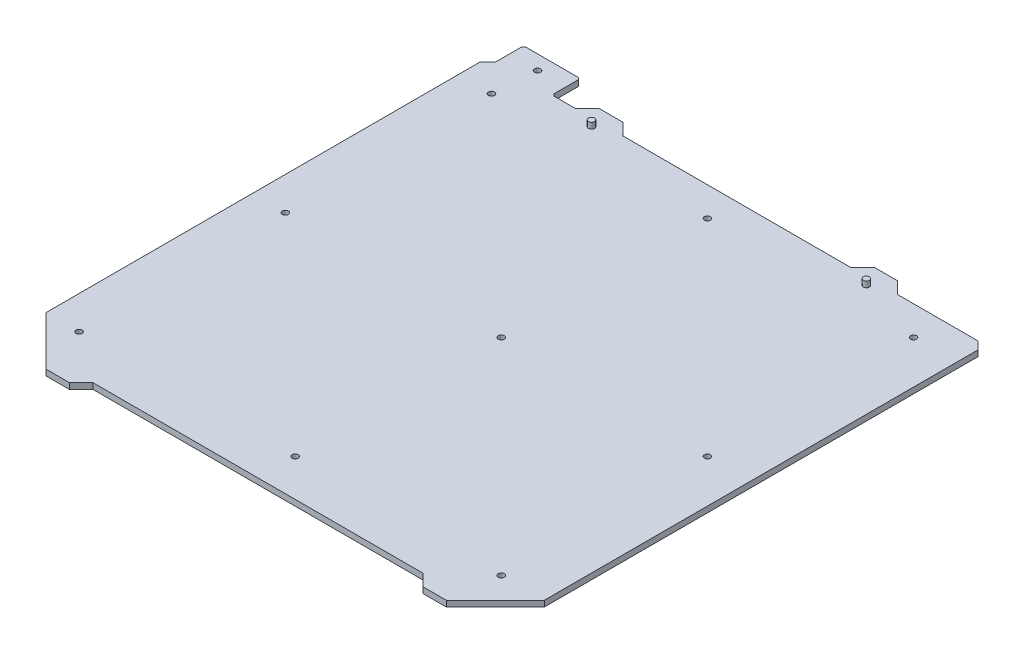
SolidWorks part; units mm, degrees
ref_plane "Front Plane" through (0, 0, 0) normal (0, 0, 1) x (1, 0, 0)
ref_plane "Top Plane" through (0, 0, 0) normal (0, 1, 0) x (1, 0, 0)
ref_plane "Right Plane" through (0, 0, 0) normal (1, 0, 0) x (0, 0, -1)
sketch "Sketch1" plane through (0, 0, 0) normal (0, 1, 0) x (1, 0, 0)
  line L0 (32.0022, 249.45) -> (32.0044, 249.45)
  line L1 (32.0044, 249.45) -> (32.0107, 249.448)
  line L2 (32.0107, 249.448) -> (32.0171, 249.447)
  line L3 (32.0171, 249.447) -> (32.019, 249.446)
  line L4 (32.019, 249.446) -> (32.0211, 249.445)
  line L5 (32.0211, 249.445) -> (32.0265, 249.442)
  line L6 (32.0265, 249.442) -> (32.0321, 249.438)
  line L7 (32.0321, 249.438) -> (32.0336, 249.437)
  line L8 (32.0336, 249.437) -> (32.0354, 249.435)
  line L9 (32.0354, 249.435) -> (33.0354, 248.435)
  line L10 (33.0354, 248.435) -> (33.0366, 248.434)
  line L11 (33.0366, 248.434) -> (33.0383, 248.432)
  line L12 (33.0383, 248.432) -> (33.0416, 248.426)
  line L13 (33.0416, 248.426) -> (33.0453, 248.421)
  line L14 (33.0453, 248.421) -> (33.0459, 248.419)
  line L15 (33.0459, 248.419) -> (33.047, 248.417)
  line L16 (33.047, 248.417) -> (33.0481, 248.411)
  line L17 (33.0481, 248.411) -> (33.0498, 248.404)
  line L18 (33.0498, 248.404) -> (33.0496, 248.402)
  line L19 (33.0496, 248.402) -> (33.05, 248.4)
  line L20 (33.05, 248.4) -> (33.05, 236.021)
  line L21 (33.05, 236.021) -> (33.9751, 235.096)
  line L22 (33.9751, 235.096) -> (34, 235.1)
  line L23 (34, 235.1) -> (45, 235.1)
  line L24 (45, 235.1) -> (45.0249, 235.096)
  line L25 (45.0249, 235.096) -> (50.9646, 241.035)
  line L26 (50.9646, 241.035) -> (50.9664, 241.037)
  line L27 (50.9664, 241.037) -> (50.9679, 241.038)
  line L28 (50.9679, 241.038) -> (50.9735, 241.042)
  line L29 (50.9735, 241.042) -> (50.9789, 241.045)
  line L30 (50.9789, 241.045) -> (50.981, 241.046)
  line L31 (50.981, 241.046) -> (50.9829, 241.047)
  line L32 (50.9829, 241.047) -> (50.9893, 241.048)
  line L33 (50.9893, 241.048) -> (50.9956, 241.05)
  line L34 (50.9956, 241.05) -> (50.9978, 241.05)
  line L35 (50.9978, 241.05) -> (51, 241.05)
  line L36 (51, 241.05) -> (63, 241.05)
  line L37 (63, 241.05) -> (63.0022, 241.05)
  line L38 (63.0022, 241.05) -> (63.0044, 241.05)
  line L39 (63.0044, 241.05) -> (63.0107, 241.048)
  line L40 (63.0107, 241.048) -> (63.0171, 241.047)
  line L41 (63.0171, 241.047) -> (63.019, 241.046)
  line L42 (63.019, 241.046) -> (63.0211, 241.045)
  line L43 (63.0211, 241.045) -> (63.0265, 241.042)
  line L44 (63.0265, 241.042) -> (63.0321, 241.038)
  line L45 (63.0321, 241.038) -> (63.0336, 241.037)
  line L46 (63.0336, 241.037) -> (63.0354, 241.035)
  line L47 (63.0354, 241.035) -> (68.9751, 235.096)
  line L48 (68.9751, 235.096) -> (69, 235.1)
  line L49 (69, 235.1) -> (185, 235.1)
  line L50 (185, 235.1) -> (185.025, 235.096)
  line L51 (185.025, 235.096) -> (190.965, 241.035)
  line L52 (190.965, 241.035) -> (190.966, 241.037)
  line L53 (190.966, 241.037) -> (190.968, 241.038)
  line L54 (190.968, 241.038) -> (190.974, 241.042)
  line L55 (190.974, 241.042) -> (190.979, 241.045)
  line L56 (190.979, 241.045) -> (190.981, 241.046)
  line L57 (190.981, 241.046) -> (190.983, 241.047)
  line L58 (190.983, 241.047) -> (190.989, 241.048)
  line L59 (190.989, 241.048) -> (190.996, 241.05)
  line L60 (190.996, 241.05) -> (190.998, 241.05)
  line L61 (190.998, 241.05) -> (191, 241.05)
  line L62 (191, 241.05) -> (203, 241.05)
  line L63 (203, 241.05) -> (203.002, 241.05)
  line L64 (203.002, 241.05) -> (203.004, 241.05)
  line L65 (203.004, 241.05) -> (203.011, 241.048)
  line L66 (203.011, 241.048) -> (203.017, 241.047)
  line L67 (203.017, 241.047) -> (203.019, 241.046)
  line L68 (203.019, 241.046) -> (203.021, 241.045)
  line L69 (203.021, 241.045) -> (203.026, 241.042)
  line L70 (203.026, 241.042) -> (203.032, 241.038)
  line L71 (203.032, 241.038) -> (203.034, 241.037)
  line L72 (203.034, 241.037) -> (203.035, 241.035)
  line L73 (203.035, 241.035) -> (208.975, 235.096)
  line L74 (208.975, 235.096) -> (209, 235.1)
  line L75 (209, 235.1) -> (250, 235.1)
  line L76 (250, 235.1) -> (250.004, 235.099)
  line L77 (250.004, 235.099) -> (250.009, 235.1)
  line L78 (250.009, 235.1) -> (250.021, 235.096)
  line L79 (250.021, 235.096) -> (250.034, 235.094)
  line L80 (250.034, 235.094) -> (250.038, 235.092)
  line L81 (250.038, 235.092) -> (250.042, 235.091)
  line L82 (250.042, 235.091) -> (250.053, 235.083)
  line L83 (250.053, 235.083) -> (250.064, 235.077)
  line L84 (250.064, 235.077) -> (250.067, 235.073)
  line L85 (250.067, 235.073) -> (250.071, 235.071)
  line L86 (250.071, 235.071) -> (254.071, 231.071)
  line L87 (254.071, 231.071) -> (254.073, 231.067)
  line L88 (254.073, 231.067) -> (254.077, 231.064)
  line L89 (254.077, 231.064) -> (254.083, 231.053)
  line L90 (254.083, 231.053) -> (254.091, 231.042)
  line L91 (254.091, 231.042) -> (254.092, 231.038)
  line L92 (254.092, 231.038) -> (254.094, 231.034)
  line L93 (254.094, 231.034) -> (254.096, 231.021)
  line L94 (254.096, 231.021) -> (254.1, 231.009)
  line L95 (254.1, 231.009) -> (254.099, 231.004)
  line L96 (254.099, 231.004) -> (254.1, 231)
  line L97 (254.1, 231) -> (254.1, 10)
  line L98 (254.1, 10) -> (254.099, 9.9957)
  line L99 (254.099, 9.9957) -> (254.1, 9.9913)
  line L100 (254.1, 9.9913) -> (254.096, 9.9787)
  line L101 (254.096, 9.9787) -> (254.094, 9.9658)
  line L102 (254.094, 9.9658) -> (254.092, 9.962)
  line L103 (254.092, 9.962) -> (254.091, 9.9577)
  line L104 (254.091, 9.9577) -> (254.083, 9.947)
  line L105 (254.083, 9.947) -> (254.077, 9.9357)
  line L106 (254.077, 9.9357) -> (254.073, 9.9329)
  line L107 (254.073, 9.9329) -> (254.071, 9.9293)
  line L108 (254.071, 9.9293) -> (229.071, -15.0707)
  line L109 (229.071, -15.0707) -> (229.067, -15.0732)
  line L110 (229.067, -15.0732) -> (229.064, -15.0766)
  line L111 (229.064, -15.0766) -> (229.053, -15.0831)
  line L112 (229.053, -15.0831) -> (229.042, -15.0906)
  line L113 (229.042, -15.0906) -> (229.038, -15.0918)
  line L114 (229.038, -15.0918) -> (229.034, -15.094)
  line L115 (229.034, -15.094) -> (229.021, -15.0962)
  line L116 (229.021, -15.0962) -> (229.009, -15.0996)
  line L117 (229.009, -15.0996) -> (229.004, -15.0992)
  line L118 (229.004, -15.0992) -> (229, -15.1)
  line L119 (229, -15.1) -> (217, -15.1)
  line L120 (217, -15.1) -> (216.996, -15.0992)
  line L121 (216.996, -15.0992) -> (216.991, -15.0996)
  line L122 (216.991, -15.0996) -> (216.979, -15.0962)
  line L123 (216.979, -15.0962) -> (216.966, -15.094)
  line L124 (216.966, -15.094) -> (216.962, -15.0918)
  line L125 (216.962, -15.0918) -> (216.958, -15.0906)
  line L126 (216.958, -15.0906) -> (216.947, -15.0831)
  line L127 (216.947, -15.0831) -> (216.936, -15.0766)
  line L128 (216.936, -15.0766) -> (216.933, -15.0732)
  line L129 (216.933, -15.0732) -> (216.929, -15.0707)
  line L130 (216.929, -15.0707) -> (210.959, -9.1)
  line L131 (210.959, -9.1) -> (43.0414, -9.1)
  line L132 (43.0414, -9.1) -> (37.0707, -15.0707)
  line L133 (37.0707, -15.0707) -> (37.0671, -15.0732)
  line L134 (37.0671, -15.0732) -> (37.0643, -15.0766)
  line L135 (37.0643, -15.0766) -> (37.053, -15.0831)
  line L136 (37.053, -15.0831) -> (37.0423, -15.0906)
  line L137 (37.0423, -15.0906) -> (37.038, -15.0918)
  line L138 (37.038, -15.0918) -> (37.0342, -15.094)
  line L139 (37.0342, -15.094) -> (37.0213, -15.0962)
  line L140 (37.0213, -15.0962) -> (37.0087, -15.0996)
  line L141 (37.0087, -15.0996) -> (37.0043, -15.0992)
  line L142 (37.0043, -15.0992) -> (37, -15.1)
  line L143 (37, -15.1) -> (25, -15.1)
  line L144 (25, -15.1) -> (24.9957, -15.0992)
  line L145 (24.9957, -15.0992) -> (24.9913, -15.0996)
  line L146 (24.9913, -15.0996) -> (24.9787, -15.0962)
  line L147 (24.9787, -15.0962) -> (24.9658, -15.094)
  line L148 (24.9658, -15.094) -> (24.962, -15.0918)
  line L149 (24.962, -15.0918) -> (24.9577, -15.0906)
  line L150 (24.9577, -15.0906) -> (24.947, -15.0831)
  line L151 (24.947, -15.0831) -> (24.9357, -15.0766)
  line L152 (24.9357, -15.0766) -> (24.9329, -15.0732)
  line L153 (24.9329, -15.0732) -> (24.9293, -15.0707)
  line L154 (24.9293, -15.0707) -> (-0.0707, 9.9293)
  line L155 (-0.0707, 9.9293) -> (-0.0732, 9.9329)
  line L156 (-0.0732, 9.9329) -> (-0.0766, 9.9357)
  line L157 (-0.0766, 9.9357) -> (-0.0831, 9.947)
  line L158 (-0.0831, 9.947) -> (-0.0906, 9.9577)
  line L159 (-0.0906, 9.9577) -> (-0.0918, 9.962)
  line L160 (-0.0918, 9.962) -> (-0.094, 9.9658)
  line L161 (-0.094, 9.9658) -> (-0.0962, 9.9787)
  line L162 (-0.0962, 9.9787) -> (-0.0996, 9.9913)
  line L163 (-0.0996, 9.9913) -> (-0.0992, 9.9957)
  line L164 (-0.0992, 9.9957) -> (-0.1, 10)
  line L165 (-0.1, 10) -> (-0.1, 231)
  line L166 (-0.1, 231) -> (-0.094, 231.034)
  line L167 (-0.094, 231.034) -> (-0.0766, 231.064)
  line L168 (-0.0766, 231.064) -> (-0.05, 231.087)
  line L169 (-0.05, 231.087) -> (-0.0174, 231.098)
  line L170 (-0.0174, 231.098) -> (0.0174, 231.098)
  line L171 (0.0174, 231.098) -> (0.025, 231.096)
  line L172 (0.025, 231.096) -> (3.95, 235.021)
  line L173 (3.95, 235.021) -> (3.95, 248.4)
  line L174 (3.95, 248.4) -> (3.9504, 248.402)
  line L175 (3.9504, 248.402) -> (3.9502, 248.404)
  line L176 (3.9502, 248.404) -> (3.9519, 248.411)
  line L177 (3.9519, 248.411) -> (3.953, 248.417)
  line L178 (3.953, 248.417) -> (3.9541, 248.419)
  line L179 (3.9541, 248.419) -> (3.9547, 248.421)
  line L180 (3.9547, 248.421) -> (3.9584, 248.426)
  line L181 (3.9584, 248.426) -> (3.9617, 248.432)
  line L182 (3.9617, 248.432) -> (3.9634, 248.434)
  line L183 (3.9634, 248.434) -> (3.9646, 248.435)
  line L184 (3.9646, 248.435) -> (4.9646, 249.435)
  line L185 (4.9646, 249.435) -> (4.9665, 249.437)
  line L186 (4.9665, 249.437) -> (4.9679, 249.438)
  line L187 (4.9679, 249.438) -> (4.9735, 249.442)
  line L188 (4.9735, 249.442) -> (4.9789, 249.445)
  line L189 (4.9789, 249.445) -> (4.981, 249.446)
  line L190 (4.981, 249.446) -> (4.9829, 249.447)
  line L191 (4.9829, 249.447) -> (4.9893, 249.448)
  line L192 (4.9893, 249.448) -> (4.9956, 249.45)
  line L193 (4.9956, 249.45) -> (4.9978, 249.45)
  line L194 (4.9978, 249.45) -> (5, 249.45)
  line L195 (5, 249.45) -> (32, 249.45)
  line L196 (32, 249.45) -> (32.0022, 249.45)
  line L197 (5.0207, 249.35) -> (4.05, 248.379)
  line L198 (4.05, 248.379) -> (4.05, 235)
  line L199 (4.05, 235) -> (4.0496, 234.998)
  line L200 (4.0496, 234.998) -> (4.0498, 234.996)
  line L201 (4.0498, 234.996) -> (4.0481, 234.989)
  line L202 (4.0481, 234.989) -> (4.047, 234.983)
  line L203 (4.047, 234.983) -> (4.0459, 234.981)
  line L204 (4.0459, 234.981) -> (4.0453, 234.979)
  line L205 (4.0453, 234.979) -> (4.0416, 234.974)
  line L206 (4.0416, 234.974) -> (4.0383, 234.968)
  line L207 (4.0383, 234.968) -> (4.0366, 234.966)
  line L208 (4.0366, 234.966) -> (4.0354, 234.965)
  line L209 (4.0354, 234.965) -> (0.0956, 231.025)
  line L210 (0.0956, 231.025) -> (0.1, 231)
  line L211 (0.1, 231) -> (0.1, 10.0414)
  line L212 (0.1, 10.0414) -> (25.0414, -14.9)
  line L213 (25.0414, -14.9) -> (36.9586, -14.9)
  line L214 (36.9586, -14.9) -> (42.9293, -8.9293)
  line L215 (42.9293, -8.9293) -> (42.9329, -8.9268)
  line L216 (42.9329, -8.9268) -> (42.9357, -8.9234)
  line L217 (42.9357, -8.9234) -> (42.947, -8.9169)
  line L218 (42.947, -8.9169) -> (42.9577, -8.9094)
  line L219 (42.9577, -8.9094) -> (42.962, -8.9082)
  line L220 (42.962, -8.9082) -> (42.9658, -8.906)
  line L221 (42.9658, -8.906) -> (42.9787, -8.9038)
  line L222 (42.9787, -8.9038) -> (42.9913, -8.9004)
  line L223 (42.9913, -8.9004) -> (42.9957, -8.9008)
  line L224 (42.9957, -8.9008) -> (43, -8.9)
  line L225 (43, -8.9) -> (211, -8.9)
  line L226 (211, -8.9) -> (211.004, -8.9008)
  line L227 (211.004, -8.9008) -> (211.009, -8.9004)
  line L228 (211.009, -8.9004) -> (211.021, -8.9038)
  line L229 (211.021, -8.9038) -> (211.034, -8.906)
  line L230 (211.034, -8.906) -> (211.038, -8.9082)
  line L231 (211.038, -8.9082) -> (211.042, -8.9094)
  line L232 (211.042, -8.9094) -> (211.053, -8.9169)
  line L233 (211.053, -8.9169) -> (211.064, -8.9234)
  line L234 (211.064, -8.9234) -> (211.067, -8.9268)
  line L235 (211.067, -8.9268) -> (211.071, -8.9293)
  line L236 (211.071, -8.9293) -> (217.041, -14.9)
  line L237 (217.041, -14.9) -> (228.959, -14.9)
  line L238 (228.959, -14.9) -> (253.9, 10.0414)
  line L239 (253.9, 10.0414) -> (253.9, 230.959)
  line L240 (253.9, 230.959) -> (249.959, 234.9)
  line L241 (249.959, 234.9) -> (209, 234.9)
  line L242 (209, 234.9) -> (208.966, 234.906)
  line L243 (208.966, 234.906) -> (208.936, 234.923)
  line L244 (208.936, 234.923) -> (208.913, 234.95)
  line L245 (208.913, 234.95) -> (208.902, 234.983)
  line L246 (208.902, 234.983) -> (208.902, 235.017)
  line L247 (208.902, 235.017) -> (208.904, 235.025)
  line L248 (208.904, 235.025) -> (202.979, 240.95)
  line L249 (202.979, 240.95) -> (191.021, 240.95)
  line L250 (191.021, 240.95) -> (185.096, 235.025)
  line L251 (185.096, 235.025) -> (185.098, 235.017)
  line L252 (185.098, 235.017) -> (185.098, 234.983)
  line L253 (185.098, 234.983) -> (185.087, 234.95)
  line L254 (185.087, 234.95) -> (185.064, 234.923)
  line L255 (185.064, 234.923) -> (185.034, 234.906)
  line L256 (185.034, 234.906) -> (185, 234.9)
  line L257 (185, 234.9) -> (69, 234.9)
  line L258 (69, 234.9) -> (68.9658, 234.906)
  line L259 (68.9658, 234.906) -> (68.9357, 234.923)
  line L260 (68.9357, 234.923) -> (68.9134, 234.95)
  line L261 (68.9134, 234.95) -> (68.9015, 234.983)
  line L262 (68.9015, 234.983) -> (68.9015, 235.017)
  line L263 (68.9015, 235.017) -> (68.9043, 235.025)
  line L264 (68.9043, 235.025) -> (62.9793, 240.95)
  line L265 (62.9793, 240.95) -> (51.0207, 240.95)
  line L266 (51.0207, 240.95) -> (45.0957, 235.025)
  line L267 (45.0957, 235.025) -> (45.0985, 235.017)
  line L268 (45.0985, 235.017) -> (45.0985, 234.983)
  line L269 (45.0985, 234.983) -> (45.0866, 234.95)
  line L270 (45.0866, 234.95) -> (45.0643, 234.923)
  line L271 (45.0643, 234.923) -> (45.0342, 234.906)
  line L272 (45.0342, 234.906) -> (45, 234.9)
  line L273 (45, 234.9) -> (34, 234.9)
  line L274 (34, 234.9) -> (33.9658, 234.906)
  line L275 (33.9658, 234.906) -> (33.9357, 234.923)
  line L276 (33.9357, 234.923) -> (33.9134, 234.95)
  line L277 (33.9134, 234.95) -> (33.9015, 234.983)
  line L278 (33.9015, 234.983) -> (33.9015, 235.017)
  line L279 (33.9015, 235.017) -> (33.9043, 235.025)
  line L280 (33.9043, 235.025) -> (32.9646, 235.965)
  line L281 (32.9646, 235.965) -> (32.9634, 235.966)
  line L282 (32.9634, 235.966) -> (32.9617, 235.968)
  line L283 (32.9617, 235.968) -> (32.9584, 235.974)
  line L284 (32.9584, 235.974) -> (32.9547, 235.979)
  line L285 (32.9547, 235.979) -> (32.9541, 235.981)
  line L286 (32.9541, 235.981) -> (32.953, 235.983)
  line L287 (32.953, 235.983) -> (32.9519, 235.989)
  line L288 (32.9519, 235.989) -> (32.9502, 235.996)
  line L289 (32.9502, 235.996) -> (32.9504, 235.998)
  line L290 (32.9504, 235.998) -> (32.95, 236)
  line L291 (32.95, 236) -> (32.95, 248.379)
  line L292 (32.95, 248.379) -> (31.9793, 249.35)
  line L293 (31.9793, 249.35) -> (5.0207, 249.35)
extrude "Boss-Extrude1" add sketch "Sketch1" along normal blind 3 contours L292 L293 L197 L198 L199 L200 L201 L202 L203 L204 L205 L206 L207 L208 L209 L210 L211 L212 L213 L214 L215 L216 L217 L218 L219 L220 L221 L222 L223 L224 L225 L226 L227 L228 L229 L230 L231 L232 L233 L234 L235 L236 L237 L238 L239 L240 L241 L242 L243 L244 L245
sketch "Sketch2" plane through (0, 3, 0) normal (0, 1, 0) x (1, 0, 0)
  line L0 (197, 231) -> (197, 240.95) construction
  line L1 (202.979, 240.95) -> (191.021, 240.95) construction
  line L2 (62.9793, 240.95) -> (51.0207, 240.95) construction
  line L3 (197, 240.95) -> (57, 240.95) construction
  line L4 (197, 240.95) -> (197, 231) construction
  line L5 (197, 231) -> (57, 231) construction
  line L6 (57, 240.95) -> (57, 231) construction
  line L7 (18.5, 242) -> (18.5, 249.35) construction
  line L8 (31.9793, 249.35) -> (5.0207, 249.35) construction
  line L9 (43, -8.9) -> (211, -8.9) construction
  line L10 (127, 10.0414) -> (127, -8.9) construction
  line L216 (127, 10.0414) -> (127, 234.9) construction
  line L217 (185, 234.9) -> (69, 234.9) construction
  line L218 (232, 10.0414) -> (232, 234.9) construction
  line L219 (249.959, 234.9) -> (209, 234.9) construction
  line L220 (17, 10.0414) -> (17, 234.9312) construction
  line L221 (232, 115.0414) -> (0.1, 115.0414) construction
  line L222 (0.1, 231) -> (0.1, 10.0414) construction
  line L223 (232, 220.0414) -> (0.1, 220.0414) construction
  line L224 (232, 10.0414) -> (0.1, 10.0414) construction
  circle A0 centre (17, 10.0414) radius 1.55
  circle A1 centre (127, 10.0414) radius 1.55
  circle A2 centre (232, 10.0414) radius 1.55
  circle A3 centre (232, 115.0414) radius 1.55
  circle A4 centre (232, 220.0414) radius 1.55
  circle A5 centre (127, 115.0414) radius 1.55
  circle A6 centre (17, 115.0414) radius 1.55
  circle A7 centre (17, 220.0414) radius 1.55
  circle A8 centre (127, 220.0414) radius 1.55
  circle A9 centre (197, 231) radius 1.55
  circle A10 centre (57, 231) radius 1.55
  circle A11 centre (18.5, 242) radius 1.55
  point P21 (57, 240.95)
  dimension "D1" = 3.1
  dimension "D2" = 3.1
  dimension "D3" = 3.1
  dimension "D4" = 3.1
  dimension "D5" = 3.1
  dimension "D6" = 3.1
  dimension "D11" = 3.1
  dimension "D12" = 3.1
  dimension "D13" = 3.1
  dimension "D15" = 3.1
  dimension "D16" = 3.1
  dimension "D18" = 3.1
  dimension "D7" = 110
  dimension "D8" = 105
  dimension "D9" = 105
  dimension "D10" = 105
  dimension "D14" = 9.95
  dimension "D17" = 7.35
extrude "Cut-Extrude1" cut sketch "Sketch2" against normal through all
sketch "Sketch3" plane through (0, 0, 0) normal (0, -1, 0) x (1, 0, 0)
  circle A0 centre (57, -231) radius 1.55 construction
  circle A1 centre (197, -231) radius 1.55 construction
  circle A2 centre (57, -231) radius 1.55
  circle A3 centre (197, -231) radius 1.55
extrude "Boss-Extrude3" add sketch "Sketch3" against normal blind 6
ref_plane "Plane1" through (127, 0, 0) normal (-1, 0, 0) x (0, 0, 1)
